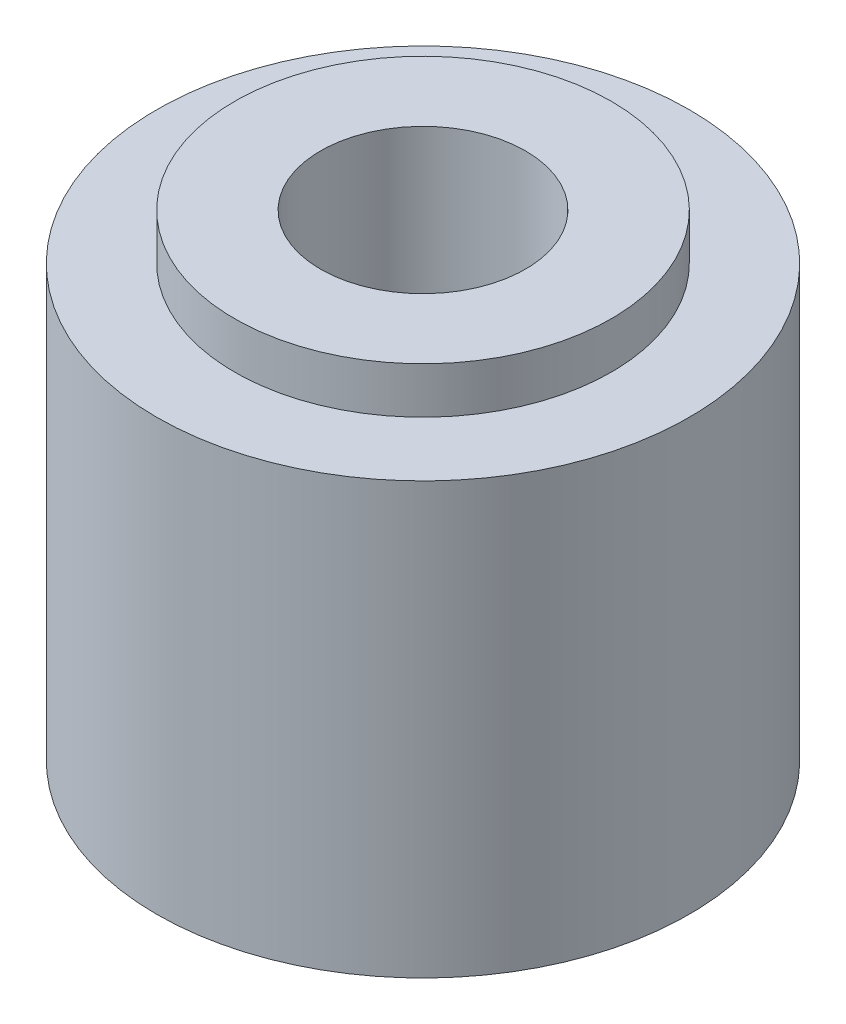
SolidWorks part; units mm, degrees
ref_plane "前视基准面" through (0, 0, 0) normal (0, 0, 1) x (1, 0, 0)
ref_plane "上视基准面" through (0, 0, 0) normal (0, 1, 0) x (1, 0, 0)
ref_plane "右视基准面" through (0, 0, 0) normal (1, 0, 0) x (0, 0, -1)
sketch "草图1" plane through (0, 0, 0) normal (0, 1, 0) x (1, 0, 0)
  circle A0 centre (0, 0) radius 19.05
  circle A1 centre (0, 0) radius 49.5
extrude "凸台-拉伸1" add sketch "草图1" along normal blind 80
sketch "草图2" plane through (0, 80, 0) normal (0, 1, 0) x (1, 0, 0)
  circle A0 centre (0, 0) radius 35
  circle A1 centre (0, 0) radius 19.05
extrude "凸台-拉伸2" add sketch "草图2" along normal blind 8.6
